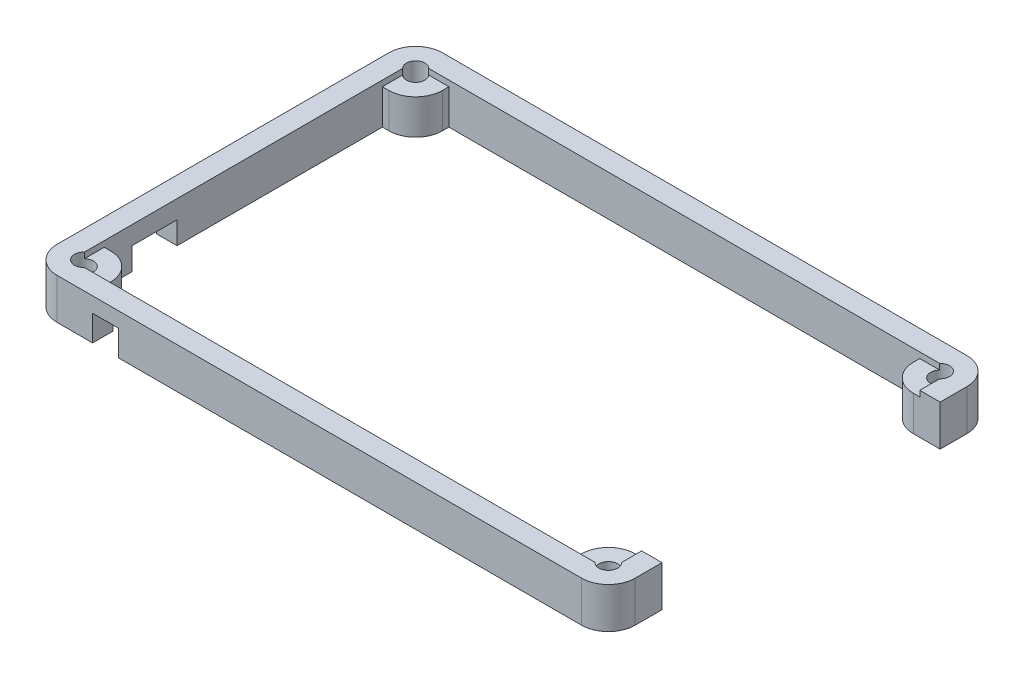
SolidWorks part; units mm, degrees
material "Rubber"
ref_plane "Front" through (0, 0, 0) normal (0, 0, 1) x (1, 0, 0)
ref_plane "Top" through (0, 0, 0) normal (0, 1, 0) x (1, 0, 0)
ref_plane "Right" through (0, 0, 0) normal (1, 0, 0) x (0, 0, -1)
sketch "Sketch1" plane through (0, 0, 0) normal (0, 1, 0) x (1, 0, 0)
  line L0 (-45, 0) -> (45, 0) construction
  line L1 (-45, 30) -> (45, 30) construction
  line L2 (-45, 30) -> (-45, -30) construction
  line L3 (-45, -30) -> (45, -30) construction
  line L4 (45, 30) -> (45, -30) construction
  line L5 (0, -30) -> (0, 30) construction
  line L6 (41.825, 26.825) -> (41.825, -26.825) construction
  line L7 (-41.825, -26.825) -> (41.825, -26.825) construction
  line L8 (-41.825, 26.825) -> (-41.825, -26.825) construction
  line L9 (-41.825, 26.825) -> (41.825, 26.825) construction
  line L10 (40.825, 25.825) -> (40.825, -25.825) construction
  line L11 (-40.825, -25.825) -> (40.825, -25.825) construction
  line L12 (-40.825, 25.825) -> (-40.825, -25.825) construction
  line L13 (-40.825, 25.825) -> (40.825, 25.825) construction
  line L14 (40.825, 21.65) -> (45, 21.65) construction
  line L15 (40.825, -21.65) -> (45, -21.65) construction
  line L16 (36.65, -25.825) -> (36.65, -30) construction
  line L17 (-36.65, -25.825) -> (-36.65, -30) construction
  line L18 (-40.825, -21.65) -> (-45, -21.65) construction
  line L19 (-36.65, 25.825) -> (-36.65, 30) construction
  line L20 (-40.825, 21.65) -> (-45, 21.65) construction
  line L21 (36.65, 25.825) -> (36.65, 30) construction
  line L22 (40.825, -25.825) -> (41.825, -25.825) construction
  circle A0 centre (-40.825, -25.825) radius 1 construction
  circle A1 centre (40.825, -25.825) radius 1 construction
  circle A2 centre (40.825, 25.825) radius 1 construction
  circle A3 centre (-40.825, 25.825) radius 1 construction
  circle A4 centre (40.825, -25.825) radius 4.175 construction
  circle A5 centre (40.825, 25.825) radius 4.175 construction
  circle A6 centre (-40.825, 25.825) radius 4.175 construction
  circle A7 centre (-40.825, -25.825) radius 4.175 construction
  dimension "D1" = 90
  dimension "D2" = 60
  dimension "D4" = 1
  dimension "D3" = 3.175
sketch "Sketch2" plane through (0, 0, 0) normal (0, 1, 0) x (1, 0, 0)
  line L0 (-45, 30) -> (-45, -30) construction
  line L1 (-45, -30) -> (45, -30) construction
  line L2 (45, 30) -> (45, -30) construction
  line L3 (-45, 30) -> (45, 30) construction
  line L4 (40.825, 21.65) -> (45, 21.65) construction
  line L5 (36.65, 25.825) -> (36.65, 30) construction
  line L6 (-36.65, 25.825) -> (-36.65, 30) construction
  line L7 (-40.825, 21.65) -> (-45, 21.65) construction
  line L8 (-36.65, -25.825) -> (-36.65, -30) construction
  line L9 (-40.825, -21.65) -> (-45, -21.65) construction
  line L10 (36.65, -25.825) -> (36.65, -30) construction
  line L11 (40.825, -21.65) -> (45, -21.65) construction
  line L16 (-45, 25.825) -> (-45, -25.825)
  line L17 (-40.825, -30) -> (40.825, -30)
  line L18 (45, 25.825) -> (45, -25.825)
  line L19 (-40.825, 30) -> (40.825, 30)
  line L20 (40.825, 21.65) -> (41.825, 21.65)
  line L21 (36.65, 25.825) -> (36.65, 26.825)
  line L22 (-36.65, 25.825) -> (-36.65, 26.825)
  line L23 (-40.825, 21.65) -> (-41.825, 21.65)
  line L24 (-36.65, -25.825) -> (-36.65, -26.825)
  line L25 (-40.825, -21.65) -> (-41.825, -21.65)
  line L26 (36.65, -25.825) -> (36.65, -26.825)
  line L27 (40.825, -21.65) -> (41.825, -21.65)
  line L28 (41.825, 26.825) -> (41.825, -26.825) construction
  line L29 (-36.65, -26.825) -> (36.65, -26.825)
  line L30 (-41.825, 26.825) -> (41.825, 26.825) construction
  line L31 (-41.825, 26.825) -> (-41.825, -26.825) construction
  line L32 (-36.65, 26.825) -> (36.65, 26.825)
  line L33 (-41.825, 21.65) -> (-41.825, -21.65)
  line L34 (41.825, 21.65) -> (41.825, -21.65)
  line L35 (-41.825, -26.825) -> (41.825, -26.825) construction
  circle A0 centre (40.825, 25.825) radius 4.175 construction
  circle A1 centre (40.825, 25.825) radius 1 construction
  circle A2 centre (-40.825, 25.825) radius 4.175 construction
  circle A3 centre (-40.825, 25.825) radius 1 construction
  circle A4 centre (-40.825, -25.825) radius 4.175 construction
  circle A5 centre (40.825, -25.825) radius 4.175 construction
  arc A6 (45, 25.825) -> (40.825, 30) centre (40.825, 25.825) ccw
  circle A7 centre (40.825, 25.825) radius 1 construction
  arc A8 (-40.825, 30) -> (-45, 25.825) centre (-40.825, 25.825) ccw
  circle A9 centre (-40.825, 25.825) radius 1 construction
  arc A10 (-36.65, -25.825) -> (-40.825, -21.65) centre (-40.825, -25.825) ccw
  arc A11 (40.825, -21.65) -> (36.65, -25.825) centre (40.825, -25.825) ccw
  circle A12 centre (-40.825, -25.825) radius 1 construction
  circle A13 centre (40.825, -25.825) radius 1 construction
  circle A14 centre (-40.825, -25.825) radius 1 construction
  circle A15 centre (40.825, -25.825) radius 1 construction
  arc A16 (-40.825, 21.65) -> (-36.65, 25.825) centre (-40.825, 25.825) ccw
  arc A17 (-45, -25.825) -> (-40.825, -30) centre (-40.825, -25.825) ccw
  arc A18 (40.825, -30) -> (45, -25.825) centre (40.825, -25.825) ccw
  arc A19 (36.65, 25.825) -> (40.825, 21.65) centre (40.825, 25.825) ccw
extrude "Boss-Extrude3" add sketch "Sketch2" along normal blind 6.35
sketch "Sketch5" plane through (-45, 0, 0) normal (-1, 0, 0) x (0, 0, 1)
  line L0 (13.825, 0) -> (25.825, 0) construction
  line L1 (25.825, 6.35) -> (25.825, 0) construction
  line L3 (17.325, 3.5) -> (10.325, 3.5)
  line L4 (17.325, 3.5) -> (17.325, -3.5)
  line L5 (17.325, -3.5) -> (10.325, -3.5)
  line L6 (10.325, 3.5) -> (10.325, -3.5)
  line L7 (17.325, 3.5) -> (10.325, -3.5) construction
  line L8 (17.325, -3.5) -> (10.325, 3.5) construction
  dimension "D1" = 12
  dimension "D2" = 7
  dimension "D3" = 7
extrude "Cut-Extrude3" cut sketch "Sketch5" against normal up to surface (3.175 mm away) up to face at (-41.825, 3.175, 0)
sketch "Sketch6" plane through (0, 0, 0) normal (0, -1, 0) x (1, 0, 0)
  circle A0 centre (40.825, 25.825) radius 1.4732
  circle A1 centre (40.825, -25.8149) radius 1.4732
  dimension "D1" = 2.9464
  dimension "D2" = 2.9464
sketch "Sketch7" plane through (0, 0, 0) normal (0, -1, 0) x (1, 0, 0)
  circle A0 centre (-40.825, -25.825) radius 1.4224
  circle A1 centre (-40.825, 25.8136) radius 1.4732
  circle A2 centre (40.825, 25.825) radius 1.4732 construction
  circle A3 centre (40.825, 25.825) radius 1.4732
  circle A5 centre (40.825, -25.8149) radius 1.4732 construction
  circle A6 centre (40.825, -25.8149) radius 1.4732
  dimension "D1" = 2.8448
  dimension "D2" = 2.9464
extrude "Cut-Extrude5" cut sketch "Sketch7" against normal up to surface (6.35 mm away) up to face at (0, 6.35, 0)
sketch "Sketch8" plane through (0, 6.35, 0) normal (0, 1, 0) x (1, 0, 0)
  line L0 (41.825, 21.65) -> (40.825, 21.65) construction
  line L1 (45, 21.65) -> (41.825, 21.65)
  line L2 (45, 21.65) -> (45, -21.65)
  line L3 (45, -21.65) -> (41.825, -21.65)
  line L4 (41.825, 21.65) -> (41.825, -21.65)
  line L5 (45, 21.65) -> (41.825, -21.65) construction
  line L6 (45, -21.65) -> (41.825, 21.65) construction
  line L7 (45, -25.825) -> (45, 25.825) construction
  point P0 (43.4125, 0)
extrude "Cut-Extrude6" cut sketch "Sketch8" against normal blind 10
sketch "Sketch9" plane through (0, 0, 30) normal (0, 0, 1) x (1, 0, 0)
  line L0 (-40.825, 0) -> (40.825, 0) construction
  line L1 (-31.2866, 4) -> (-35.2866, 4)
  line L2 (-31.2866, 4) -> (-31.2866, 0)
  line L3 (-31.2866, 0) -> (-35.2866, 0)
  line L4 (-35.2866, 4) -> (-35.2866, 0)
  line L5 (-31.2866, 4) -> (-35.2866, 0) construction
  line L6 (-31.2866, 0) -> (-35.2866, 4) construction
  dimension "D1" = 4
  dimension "D2" = 5.5384
  dimension "D3" = 4
extrude "Cut-Extrude8" cut sketch "Sketch9" against normal blind 4
sketch "Sketch10" plane through (0, 6.35, 0) normal (0, 1, 0) x (1, 0, 0)
  line L0 (-41.825, -21.65) -> (-40.825, -21.65) construction
  line L1 (-36.65, 26.825) -> (-41.825, 26.825)
  line L3 (-36.65, 26.825) -> (-36.65, 21.65)
  line L4 (-36.65, 21.65) -> (-41.825, 21.65)
  line L5 (-41.825, 26.825) -> (-41.825, 21.65)
  line L7 (-36.65, -26.825) -> (-41.825, -26.825)
  line L8 (-36.65, -26.825) -> (-36.65, -21.65)
  line L11 (-36.65, -21.65) -> (-41.825, -21.65)
  line L12 (-41.825, -26.825) -> (-41.825, -21.65)
  line L14 (41.83, -21.65) -> (36.65, -21.65)
  line L15 (41.83, -21.65) -> (41.83, -26.825)
  line L16 (41.83, -26.825) -> (36.65, -26.825)
  line L17 (36.65, -21.65) -> (36.65, -26.825)
  line L18 (36.65, 26.825) -> (41.83, 26.825)
  line L19 (36.65, 26.825) -> (36.65, 21.65)
  line L20 (36.65, 21.65) -> (41.83, 21.65)
  line L21 (41.83, 26.825) -> (41.83, 21.65)
  dimension "D1" = 5.18
  dimension "D2" = 5.18
extrude "Cut-Extrude9" cut sketch "Sketch10" against normal blind 0.9
